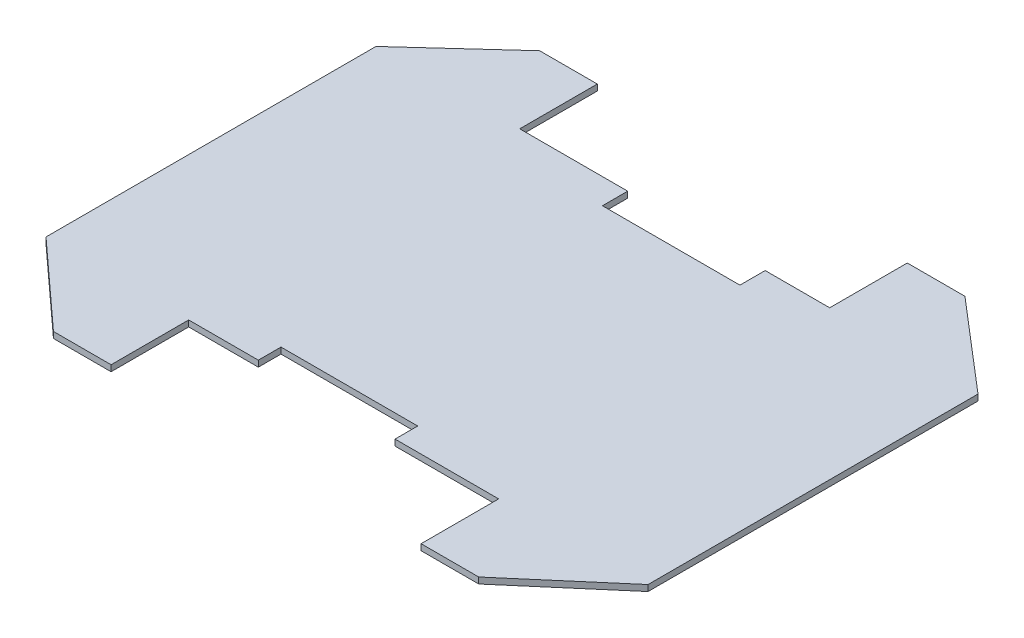
SolidWorks part; units mm, degrees
ref_plane "Спереди" through (0, 0, 0) normal (0, 0, 1) x (1, 0, 0)
ref_plane "Сверху" through (0, 0, 0) normal (0, 1, 0) x (1, 0, 0)
ref_plane "Справа" through (0, 0, 0) normal (1, 0, 0) x (0, 0, -1)
sketch "Эскиз1" plane through (0, 0, 0) normal (0, 1, 0) x (1, 0, 0)
  line L0 (-43.1698, 75.1415) -> (-43.1698, 52.3492)
  line L1 (-269.7922, 74.6607) -> (-269.7922, -223.012)
  line L2 (139.0683, -293.4928) -> (191.0683, -293.4928)
  line L3 (-140.5865, 145.1415) -> (-192.5865, 145.1415)
  line L4 (139.0683, -223.4928) -> (139.0683, -293.4928)
  line L5 (139.0683, 145.1415) -> (191.0683, 145.1415)
  line L6 (-140.5865, 75.1415) -> (-140.5865, 145.1415)
  line L7 (-0.7591, -12.2026) -> (-0.7591, 227.1905) construction
  line L8 (273.3416, 74.6607) -> (273.3416, -223.012)
  line L9 (-140.5865, -223.4928) -> (-77.7544, -223.4928)
  line L10 (139.0683, 75.1415) -> (139.0683, 145.1415)
  line L11 (-140.5865, 75.1415) -> (-43.1698, 75.1415)
  line L12 (-140.5865, -223.4928) -> (-140.5865, -293.4928)
  line L13 (-140.5865, -293.4928) -> (-192.5865, -293.4928)
  line L14 (-43.1698, 52.3492) -> (80.8757, 52.3492)
  line L15 (80.8757, 75.1415) -> (139.0683, 75.1415)
  line L16 (80.8757, 52.3492) -> (80.8757, 75.1415)
  line L17 (-326.8393, -74.1757) -> (107.7018, -74.1757) construction
  line L18 (45.5875, -203.0558) -> (45.5875, -223.4928)
  line L19 (-77.7544, -203.0558) -> (45.5875, -203.0558)
  line L20 (-77.7544, -223.4928) -> (-77.7544, -203.0558)
  line L21 (45.5875, -223.4928) -> (139.0683, -223.4928)
  line L22 (-269.7922, 74.6607) -> (-192.5865, 145.1415)
  line L23 (-269.7922, -223.012) -> (-192.5865, -293.4928)
  line L24 (-263.7922, 74.6607) -> (-387.0064, 74.6607) construction
  line L25 (-269.7922, -223.012) -> (-392.2998, -223.012) construction
  line L26 (273.3416, -223.012) -> (191.0683, -293.4928)
  line L27 (273.3416, 74.6607) -> (191.0683, 145.1415)
extrude "Вытянуть1" add sketch "Эскиз1" along normal blind 5.5
